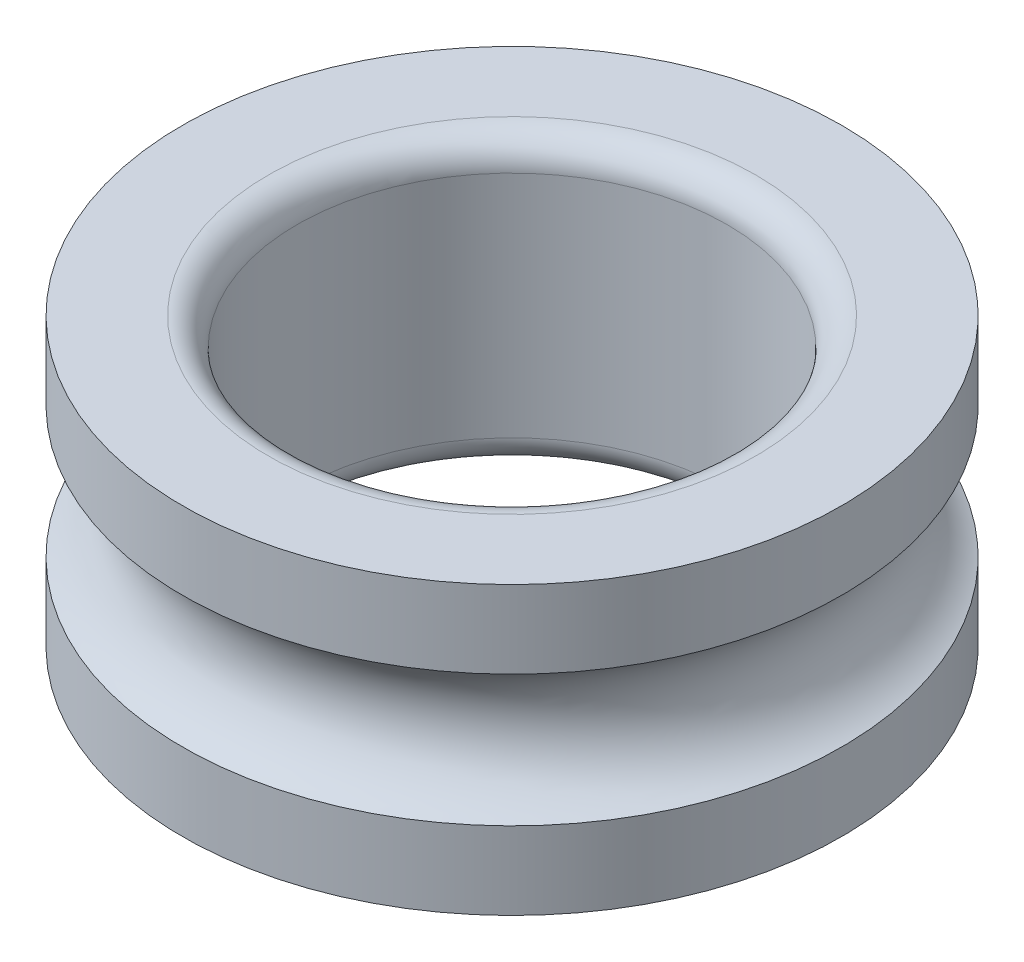
SolidWorks part; units mm, degrees
ref_plane "Front Plane" through (0, 0, 0) normal (1, 0, 0) x (0, 1, 0)
ref_plane "Top Plane" through (0, 0, 0) normal (0, 0, 1) x (0, 1, 0)
ref_plane "Right Plane" through (0, 0, 0) normal (0, 1, 0) x (-1, 0, 0)
sketch "Sketch1" plane through (0, 0, 0) normal (1, 0, 0) x (0, 1, 0)
  line L0 (-16.2569, 0) -> (18.48, 0) construction
  line L1 (0, 14.4197) -> (0, -14.7437) construction
  line L2 (-5, 12.5) -> (5, 12.5) construction
  line L5 (-4, 7.5) -> (4, 7.5)
  line L8 (-5, 11.5) -> (-2.2913, 11.5)
  line L9 (-5, 11.5) -> (-5, 8.5)
  line L10 (5, 11.5) -> (5, 8.5)
  line L11 (2.2913, 11.5) -> (5, 11.5)
  arc A0 (-2.2913, 11.5) -> (2.2913, 11.5) centre (0, 12.5) ccw
  arc A1 (4, 7.5) -> (5, 8.5) centre (4, 8.5) ccw
  arc A2 (-5, 8.5) -> (-4, 7.5) centre (-4, 8.5) ccw
  point P12 (0, 0)
  point P17 (5, 7.5)
  point P20 (-5, 7.5)
  dimension "D4" = 5
  dimension "D6" = 4.5826
  dimension "D7" = 1
  dimension "D1" = 1
  dimension "D2" = 10
  dimension "D3" = 5
  dimension "D5" = 7.5
revolve "Revolve1" add sketch "Sketch1" angle 360 about L0
